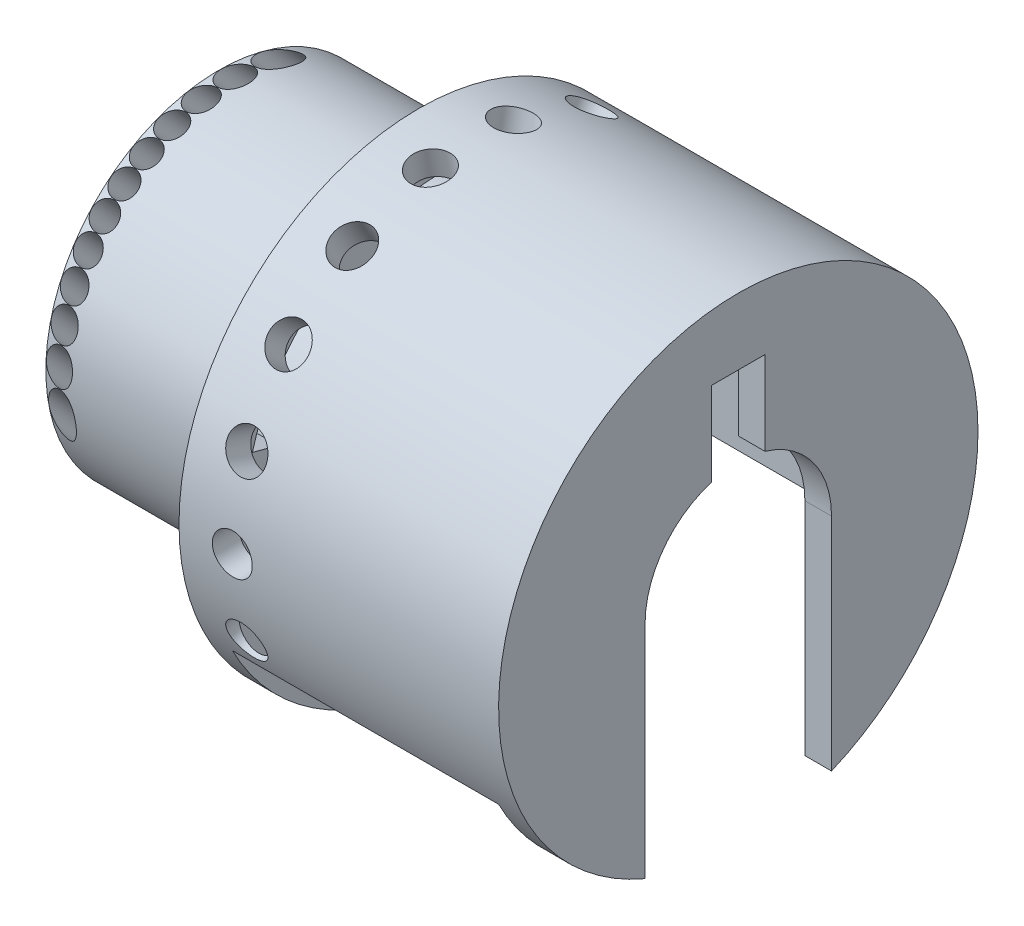
SolidWorks part; units mm, degrees
material "ABS"
ref_plane "Спереди" through (0, 0, 0) normal (0, 0, 1) x (1, 0, 0)
ref_plane "Сверху" through (0, 0, 0) normal (0, 1, 0) x (1, 0, 0)
ref_plane "Справа" through (0, 0, 0) normal (1, 0, 0) x (0, 0, -1)
sketch "Эскиз1" plane through (0, 0, 0) normal (0, 0, 1) x (1, 0, 0)
  line L0 (0, 0) -> (0, 6.5)
  line L1 (0, 6.5) -> (7.5, 6.5)
  line L2 (7.5, 6.5) -> (7.5, 9)
  line L3 (7.5, 9) -> (19.5, 9)
  line L4 (19.5, 9) -> (19.5, 3.5)
  line L5 (19.5, 3.5) -> (18.5, 3.5)
  line L6 (1, 0) -> (1, 5.5)
  line L7 (1, 5.5) -> (8.5, 5.5)
  line L8 (8.5, 5.5) -> (8.5, 8)
  line L9 (8.5, 8) -> (18.5, 8)
  line L10 (18.5, 8) -> (18.5, 3.5)
  line L11 (1, 0) -> (0, 0)
  dimension "D1" = 1
  dimension "D2" = 1
  dimension "D3" = 1
  dimension "D4" = 1
  dimension "D5" = 1
  dimension "D6" = 7.5
  dimension "D7" = 3.5
  dimension "D8" = 8
  dimension "D9" = 10
  dimension "D10" = 6.5
revolve "Повернуть1" add sketch "Эскиз1" angle 360 about L11
sketch "Эскиз2" plane through (19.5, 0, 0) normal (1, 0, 0) x (0, 0, -1)
  line L0 (-3.5, 0) -> (-3.5, -10)
  line L1 (-3.5, -10) -> (3.5, -10)
  line L2 (3.5, -10) -> (3.5, 0)
  line L3 (-3.5, 0) -> (3.5, 0)
  line L4 (-1, 3) -> (-1, 6.5)
  line L5 (-1, 6.5) -> (1, 6.5)
  line L6 (1, 6.5) -> (1, 3)
  line L7 (1, 3) -> (-1, 3)
  circle A0 centre (0, 0) radius 3.5 construction
  dimension "D1" = 2
  dimension "D2" = 1
  dimension "D3" = 6.5
  dimension "D4" = 10
  dimension "D5" = 3
extrude "Вырез-Вытянуть1" cut sketch "Эскиз2" against normal blind 11
sketch "Эскиз3" plane through (0, 0, 0) normal (0, 1, 0) x (1, 0, 0)
  line L0 (18.5, 8) -> (8.5, 8)
  line L1 (18.5, 8) -> (18.5, -8)
  line L2 (8.5, 8) -> (8.5, -8)
  line L3 (18.5, -8) -> (8.5, -8)
  line L4 (18.5, 8) -> (8.5, -8) construction
  line L5 (8.5, 8) -> (18.5, -8) construction
  point P1 (13.5, 0)
  dimension "D1" = 16
  dimension "D2" = 8
  dimension "D3" = 10
  dimension "D4" = 8.5
extrude "Вырез-Вытянуть2" cut sketch "Эскиз3" against normal blind 10
sketch "Эскиз5" plane through (0, 0, 0) normal (0, 0, 1) x (1, 0, 0)
  line L0 (0, 0) -> (50000, 0) construction
  circle A0 centre (9.5, 0) radius 0.75
  dimension "D2" = 1.5
  dimension "D1" = 9.5
extrude "Вырез-Вытянуть4" cut sketch "Эскиз5" against normal blind 10
pattern_circular "Круговой массив2" count 18 over 360 about axis through (0, 0, 0) along (1, 0, 0) of "Вырез-Вытянуть4"
sketch "Эскиз6" plane through (0, 0, 0) normal (-1, 0, 0) x (0, 0, 1)
  line L0 (0, 0) -> (50000, 0) construction
  line L1 (0, 0) -> (34099.918, 36567.6851) construction
  dimension "D1" = 47
ref_plane "Плоскость1" through (0, 0, 0) normal (0, 0.7314, 0.682) x (1, 0, 0)
sketch "Эскиз7" plane through (0, 0, 0) normal (0, 0.7314, 0.682) x (1, 0, 0)
  circle A0 centre (0.5, -5.5) radius 0.49
  circle A1 centre (0.5, -4.5) radius 0.49
  circle A2 centre (0.5, -3.5) radius 0.49
  circle A3 centre (0.5, -2.5) radius 0.49
  circle A4 centre (0.5, -1.5) radius 0.49
  circle A5 centre (0.5, -0.5) radius 0.49
  circle A6 centre (0.5, 0.5) radius 0.49
  circle A7 centre (0.5, 1.5) radius 0.49
  circle A8 centre (0.5, 2.5) radius 0.49
  circle A9 centre (0.5, 3.5) radius 0.49
  circle A10 centre (0.5, 4.5) radius 0.49
  circle A11 centre (0.5, 5.5) radius 0.49
  dimension "D1" = 0.98
  dimension "D5" = 1
  dimension "D2" = 5.5
  dimension "D3" = 0.5
  dimension "D4" = 12
extrude "Вырез-Вытянуть5" cut sketch "Эскиз7" along normal blind 10
sketch "Эскиз8" plane through (7.5, 0, 0) normal (-1, 0, 0) x (0, 0, 1)
  line L0 (0, 0) -> (0, 50000) construction
  line L1 (0, 0) -> (12940.9523, 48296.2913) construction
  line L2 (0, 0) -> (-12940.9523, 48296.2913) construction
  line L3 (-1.9411, 7.2444) -> (-1.6823, 6.2785)
  line L4 (1.9411, 7.2444) -> (1.6823, 6.2785)
  line L5 (5.3033, 5.3033) -> (4.5962, 4.5962)
  line L6 (7.2444, 1.9411) -> (6.2785, 1.6823)
  line L7 (7.2444, -1.9411) -> (6.2785, -1.6823)
  line L8 (5.3033, -5.3033) -> (4.5962, -4.5962)
  line L9 (1.9411, -7.2444) -> (1.6823, -6.2785)
  line L10 (-1.9411, -7.2444) -> (-1.6823, -6.2785)
  line L11 (-5.3033, -5.3033) -> (-4.5962, -4.5962)
  line L12 (-7.2444, -1.9411) -> (-6.2785, -1.6823)
  line L13 (-7.2444, 1.9411) -> (-6.2785, 1.6823)
  line L14 (-5.3033, 5.3033) -> (-4.5962, 4.5962)
  arc A0 (-1.9411, 7.2444) -> (1.9411, 7.2444) centre (0, 0) cw
  arc A1 (-1.6823, 6.2785) -> (1.6823, 6.2785) centre (0, 0) cw
  arc A3 (5.3033, 5.3033) -> (7.2444, 1.9411) centre (0, 0) cw
  arc A4 (4.5962, 4.5962) -> (6.2785, 1.6823) centre (0, 0) cw
  arc A5 (7.2444, -1.9411) -> (5.3033, -5.3033) centre (0, 0) cw
  arc A6 (6.2785, -1.6823) -> (4.5962, -4.5962) centre (0, 0) cw
  arc A7 (1.9411, -7.2444) -> (-1.9411, -7.2444) centre (0, 0) cw
  arc A8 (1.6823, -6.2785) -> (-1.6823, -6.2785) centre (0, 0) cw
  arc A9 (-5.3033, -5.3033) -> (-7.2444, -1.9411) centre (0, 0) cw
  arc A10 (-4.5962, -4.5962) -> (-6.2785, -1.6823) centre (0, 0) cw
  arc A11 (-7.2444, 1.9411) -> (-5.3033, 5.3033) centre (0, 0) cw
  arc A12 (-6.2785, 1.6823) -> (-4.5962, 4.5962) centre (0, 0) cw
  point P35 (0, 0)
  dimension "D1" = 6.5
  dimension "D2" = 7.5
  dimension "D3" = 30
  dimension "D4" = 15
  dimension "D5" = 6
extrude "Вырез-Вытянуть6" cut sketch "Эскиз8" against normal blind 1
